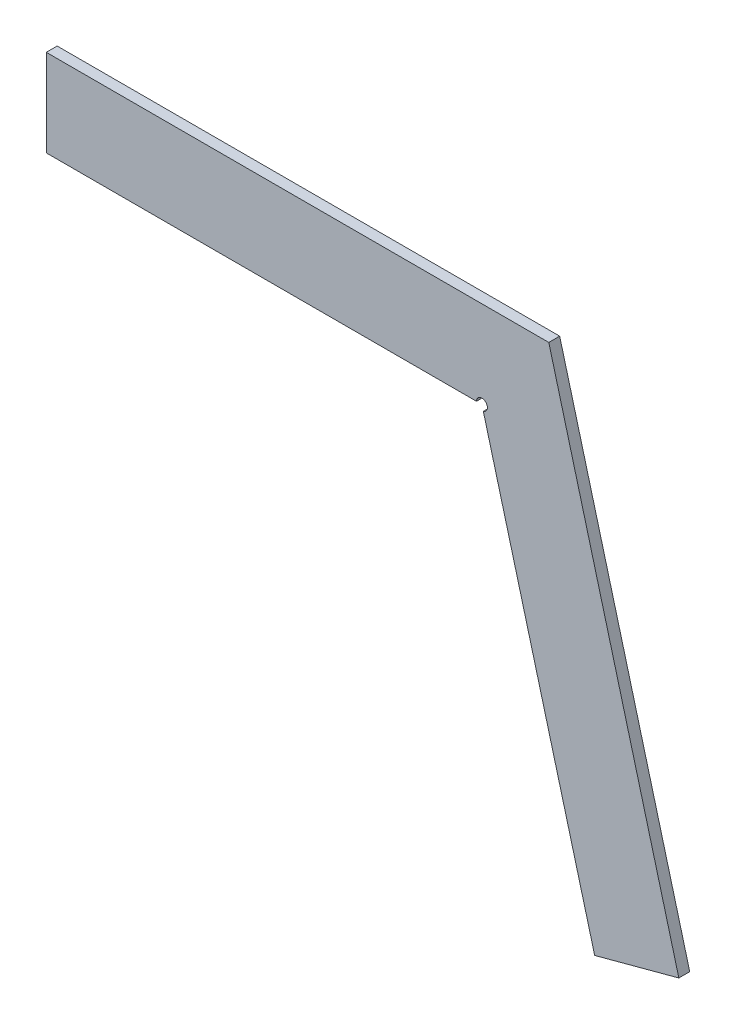
SolidWorks part; units mm, degrees
ref_plane "Plan de face" through (0, 0, 0) normal (0, 0, 1) x (1, 0, 0)
ref_plane "Plan de dessus" through (0, 0, 0) normal (0, 1, 0) x (1, 0, 0)
ref_plane "Plan de droite" through (0, 0, 0) normal (1, 0, 0) x (0, 0, -1)
sketch "Esquisse1" plane through (0, 0, 0) normal (0, 0, 1) x (1, 0, 0)
  line L0 (0, 0) -> (0, -40)
  line L1 (0, -40) -> (200, -40)
  line L2 (200, -40) -> (251.7638, -233.1852)
  line L3 (251.7638, -233.1852) -> (290.4008, -222.8324)
  line L4 (290.4008, -222.8324) -> (230.6931, 0)
  line L5 (230.6931, 0) -> (0, 0)
  point P8 (100, -40)
  dimension "D1" = 105
  dimension "D2" = 40
  dimension "D3" = 40
  dimension "D4" = 200
  dimension "D5" = 200
extrude "Boss.-Extru.1" add sketch "Esquisse1" along normal blind 5
sketch "Esquisse2" plane through (0, 0, 5) normal (0, 0, 1) x (1, 0, 0)
  circle A0 centre (200, -40) radius 2.5
  dimension "D1" = 5
extrude "Enlèv. mat.-Extru.1" cut sketch "Esquisse2" against normal through all
